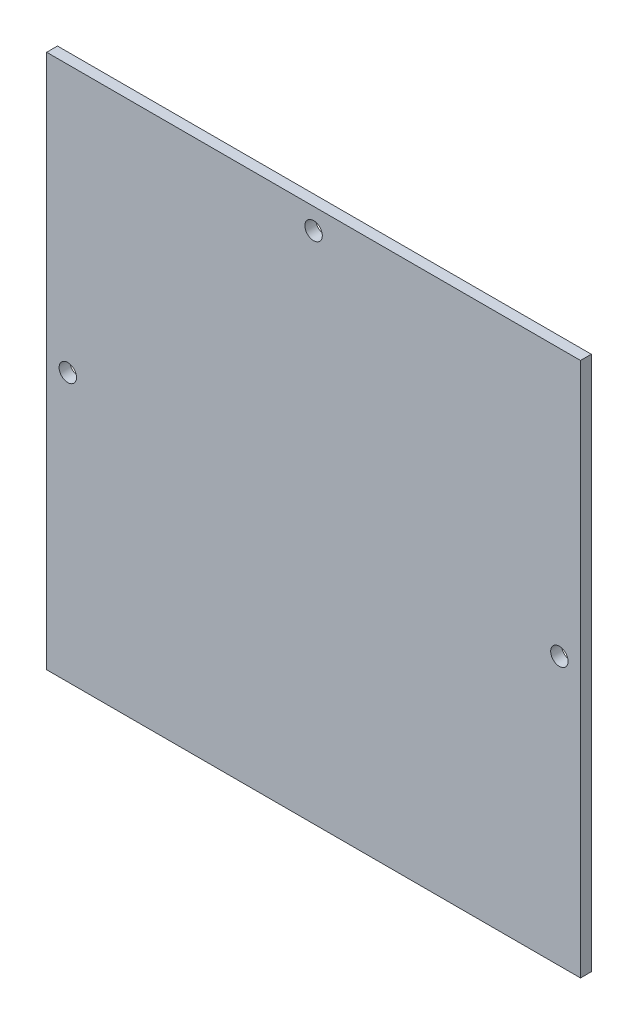
SolidWorks part; units mm, degrees
material "PCB Multi Layer"
ref_plane "Front Plane" through (0, 0, 0) normal (0, 0, 1) x (1, 0, 0)
ref_plane "Top Plane" through (0, 0, 0) normal (0, 1, 0) x (1, 0, 0)
ref_plane "Right Plane" through (0, 0, 0) normal (1, 0, 0) x (0, 0, -1)
sketch "Sketch1" plane through (0, 0, 0) normal (0, 0, 1) x (1, 0, 0)
  line L1 (0, 0) -> (88.865, 0)
  line L2 (0, 0) -> (0, 89.025)
  line L3 (0, 89.025) -> (88.865, 89.025)
  line L4 (88.865, 0) -> (88.865, 89.025)
  dimension "D1" = 88.865
  dimension "D2" = 89.025
extrude "Boss-Extrude1" add sketch "Sketch1" along normal blind 1.8
hole_wizard "M2.5 Clearance Hole1" positions "Sketch2" profile "Sketch3" hole size "M2.5" standard "ANSI Metric"
sketch "Sketch2" plane through (0, 0, 1.8) normal (0, 0, 1) x (1, 0, 0)
  line L0 (88.865, 89.025) -> (0, 89.025) construction
  line L1 (88.865, 0) -> (88.865, 89.025) construction
  line L2 (0, 89.025) -> (0, 0) construction
  point P0 (44.4325, 85.525)
  point P2 (3.52, 44.6125)
  point P4 (85.345, 44.6125)
  dimension "D1" = 3.5
  dimension "D2" = 3.52
  dimension "D3" = 3.52
  dimension "D4" = 44.4125
  dimension "D5" = 44.4325
sketch "Sketch3" plane through (44.4325, 85.525, 1.8) normal (1, 0, 0) x (0, -1, 0)
  line L0 (0, 0) -> (0, 4.8712)
  line L1 (0, 4.8712) -> (1.45, 4)
  line L2 (1.45, 4) -> (1.45, 0)
  line L5 (1.45, 0) -> (0, 0)
  line L10 (0, 4.8712) -> (-1.45, 4) construction
  line L11 (0, -6.35) -> (0, 107.95) construction
  dimension "Hole Dia." = 2.9
  dimension "Hole Depth" = 4
  dimension "Drill Angle" = 118
